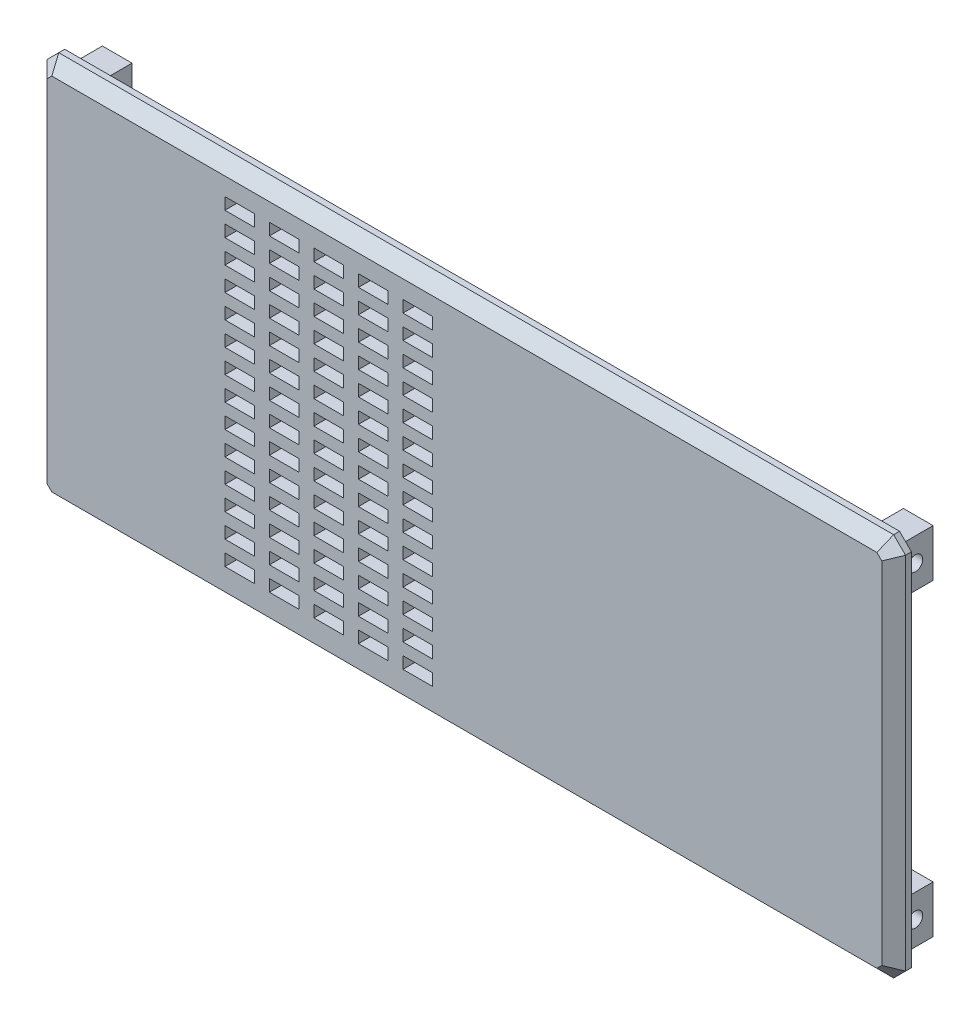
SolidWorks part; units mm, degrees
ref_plane "Спереди" through (0, 0, 0) normal (0, 0, 1) x (1, 0, 0)
ref_plane "Сверху" through (0, 0, 0) normal (0, 1, 0) x (1, 0, 0)
ref_plane "Справа" through (0, 0, 0) normal (1, 0, 0) x (0, 0, -1)
sketch "Эскиз1" plane through (0, 0, 0) normal (0, 0, 1) x (1, 0, 0)
  line L0 (-72.35, 30.35) -> (-70.35, 32.35)
  line L1 (70.35, -32.35) -> (-70.35, -32.35)
  line L2 (72.35, -30.35) -> (72.35, 30.35)
  line L3 (70.35, 32.35) -> (-70.35, 32.35)
  line L4 (-72.35, -30.35) -> (-72.35, 30.35)
  line L5 (-72.35, -30.35) -> (-70.35, -32.35)
  line L6 (70.35, -32.35) -> (72.35, -30.35)
  line L7 (70.35, 32.35) -> (72.35, 30.35)
extrude "Бобышка-Вытянуть1" add sketch "Эскиз1" along normal blind 3
sketch "Эскиз2" plane through (0, 0, 0) normal (0, 0, -1) x (-1, 0, 0)
  line L0 (-70, 30) -> (70, 30)
  line L1 (-70.35, 30.35) -> (70.35, 30.35) construction
  line L2 (-70.35, 30.35) -> (-70.35, -30.35) construction
  line L3 (-70.35, -30.35) -> (70.35, -30.35) construction
  line L4 (70.35, 30.35) -> (70.35, -30.35) construction
  line L5 (70, 30) -> (70, -30)
  line L6 (-70, -30) -> (70, -30)
  line L7 (-70, 30) -> (-70, -30)
  line L8 (-68, 28) -> (68, 28)
  line L9 (68, 28) -> (68, -28)
  line L10 (-68, -28) -> (68, -28)
  line L11 (-68, 28) -> (-68, -28)
  dimension "D1" = 0.35
  dimension "D2" = 2
extrude "Бобышка-Вытянуть2" add sketch "Эскиз2" along normal blind 2
sketch "Эскиз3" plane through (0, 0, 0) normal (0, 0, -1) x (-1, 0, 0)
  line L0 (-72.35, 0) -> (72.35, 0) construction
  line L1 (-72.35, -30.35) -> (-72.35, 30.35) construction
  line L2 (72.35, 30.35) -> (72.35, -30.35) construction
  line L3 (0, 32.35) -> (0, -32.35) construction
  line L4 (-70.35, 32.35) -> (70.35, 32.35) construction
  line L5 (70.35, -32.35) -> (-70.35, -32.35) construction
  line L6 (-70, 30) -> (-70, -30) construction
  line L7 (-70, 30) -> (-65, 30)
  line L8 (-70, 30) -> (-70, 22)
  line L9 (-70, 22) -> (-65, 22)
  line L10 (-65, 30) -> (-65, 22)
  line L11 (70, 30) -> (-70, 30) construction
  line L12 (-65, -30) -> (-65, -22)
  line L13 (-70, -22) -> (-65, -22)
  line L14 (-70, -30) -> (-70, -22)
  line L15 (-70, -30) -> (-65, -30)
  line L16 (70, -30) -> (65, -30)
  line L17 (70, -30) -> (70, -22)
  line L18 (70, -22) -> (65, -22)
  line L19 (65, -30) -> (65, -22)
  line L20 (65, 30) -> (65, 22)
  line L21 (70, 22) -> (65, 22)
  line L22 (70, 30) -> (70, 22)
  line L23 (70, 30) -> (65, 30)
  dimension "D1" = 5
  dimension "D2" = 8
extrude "Бобышка-Вытянуть3" add sketch "Эскиз3" along normal blind 6
sketch "Эскиз4" plane through (70, 0, 0) normal (1, 0, 0) x (0, 0, -1)
  line L0 (0, 30) -> (6, 22) construction
  line L1 (6, 30) -> (0, 22) construction
  line L2 (0, -30.35) -> (0, 30.35) construction
  line L3 (6, -22) -> (0, -30) construction
  line L4 (6, -30) -> (0, -22) construction
  line L5 (0, 30) -> (0, -30) construction
  line L6 (2, -22) -> (0, -22) construction
  line L7 (2, 22) -> (0, 22) construction
  circle A0 centre (3, 26) radius 1.25
  circle A1 centre (3, -26) radius 1.25
  dimension "D1" = 2.5
extrude "Вырез-Вытянуть1" cut sketch "Эскиз4" against normal up to surface (140 mm away)
sketch "Эскиз6" plane through (0, 0, 3) normal (0, 0, 1) x (1, 0, 0)
  line L0 (-5.35, -32.35) -> (-5.35, 32.35) construction
  line L1 (-70.35, -32.35) -> (70.35, -32.35) construction
  line L2 (70.35, 32.35) -> (-70.35, 32.35) construction
  line L3 (-40.35, -32.35) -> (-40.35, 32.35) construction
  line L4 (-72.35, 30.35) -> (-72.35, -30.35) construction
  line L5 (-40.35, 27.35) -> (-5.35, 27.35) construction
  line L6 (-27.85, 27.35) -> (-27.85, 25.35)
  line L7 (-40.35, 27.35) -> (-35.35, 27.35)
  line L8 (-40.35, 27.35) -> (-40.35, 25.35)
  line L9 (-40.35, 25.35) -> (-35.35, 25.35)
  line L10 (-35.35, 27.35) -> (-35.35, 25.35)
  line L11 (-32.85, 27.35) -> (-27.85, 27.35)
  line L12 (-32.85, 25.35) -> (-27.85, 25.35)
  line L13 (-32.85, 27.35) -> (-32.85, 25.35)
  line L14 (-20.35, 27.35) -> (-20.35, 25.35)
  line L15 (-25.35, 27.35) -> (-20.35, 27.35)
  line L16 (-25.35, 25.35) -> (-20.35, 25.35)
  line L17 (-25.35, 27.35) -> (-25.35, 25.35)
  line L18 (-12.85, 27.35) -> (-12.85, 25.35)
  line L19 (-17.85, 27.35) -> (-12.85, 27.35)
  line L20 (-17.85, 25.35) -> (-12.85, 25.35)
  line L21 (-17.85, 27.35) -> (-17.85, 25.35)
  line L22 (-5.35, 27.35) -> (-5.35, 25.35)
  line L23 (-10.35, 27.35) -> (-5.35, 27.35)
  line L24 (-10.35, 25.35) -> (-5.35, 25.35)
  line L25 (-10.35, 27.35) -> (-10.35, 25.35)
  line L26 (-27.85, 23.35) -> (-27.85, 21.35)
  line L27 (-32.85, 23.35) -> (-27.85, 23.35)
  line L28 (-32.85, 21.35) -> (-27.85, 21.35)
  line L29 (-32.85, 23.35) -> (-32.85, 21.35)
  line L30 (-20.35, 23.35) -> (-20.35, 21.35)
  line L31 (-25.35, 23.35) -> (-20.35, 23.35)
  line L32 (-25.35, 21.35) -> (-20.35, 21.35)
  line L33 (-25.35, 23.35) -> (-25.35, 21.35)
  line L34 (-12.85, 23.35) -> (-12.85, 21.35)
  line L35 (-17.85, 23.35) -> (-12.85, 23.35)
  line L36 (-17.85, 21.35) -> (-12.85, 21.35)
  line L37 (-17.85, 23.35) -> (-17.85, 21.35)
  line L38 (-5.35, 23.35) -> (-5.35, 21.35)
  line L39 (-10.35, 23.35) -> (-5.35, 23.35)
  line L40 (-10.35, 21.35) -> (-5.35, 21.35)
  line L41 (-10.35, 23.35) -> (-10.35, 21.35)
  line L42 (-27.85, 19.35) -> (-27.85, 17.35)
  line L43 (-32.85, 19.35) -> (-27.85, 19.35)
  line L44 (-32.85, 17.35) -> (-27.85, 17.35)
  line L45 (-32.85, 19.35) -> (-32.85, 17.35)
  line L46 (-20.35, 19.35) -> (-20.35, 17.35)
  line L47 (-25.35, 19.35) -> (-20.35, 19.35)
  line L48 (-25.35, 17.35) -> (-20.35, 17.35)
  line L49 (-25.35, 19.35) -> (-25.35, 17.35)
  line L50 (-12.85, 19.35) -> (-12.85, 17.35)
  line L51 (-17.85, 19.35) -> (-12.85, 19.35)
  line L52 (-17.85, 17.35) -> (-12.85, 17.35)
  line L53 (-17.85, 19.35) -> (-17.85, 17.35)
  line L54 (-5.35, 19.35) -> (-5.35, 17.35)
  line L55 (-10.35, 19.35) -> (-5.35, 19.35)
  line L56 (-10.35, 17.35) -> (-5.35, 17.35)
  line L57 (-10.35, 19.35) -> (-10.35, 17.35)
  line L58 (-27.85, 15.35) -> (-27.85, 13.35)
  line L59 (-32.85, 15.35) -> (-27.85, 15.35)
  line L60 (-32.85, 13.35) -> (-27.85, 13.35)
  line L61 (-32.85, 15.35) -> (-32.85, 13.35)
  line L62 (-20.35, 15.35) -> (-20.35, 13.35)
  line L63 (-25.35, 15.35) -> (-20.35, 15.35)
  line L64 (-25.35, 13.35) -> (-20.35, 13.35)
  line L65 (-25.35, 15.35) -> (-25.35, 13.35)
  line L66 (-12.85, 15.35) -> (-12.85, 13.35)
  line L67 (-17.85, 15.35) -> (-12.85, 15.35)
  line L68 (-17.85, 13.35) -> (-12.85, 13.35)
  line L69 (-17.85, 15.35) -> (-17.85, 13.35)
  line L70 (-5.35, 15.35) -> (-5.35, 13.35)
  line L71 (-10.35, 15.35) -> (-5.35, 15.35)
  line L72 (-10.35, 13.35) -> (-5.35, 13.35)
  line L73 (-10.35, 15.35) -> (-10.35, 13.35)
  line L74 (-27.85, 11.35) -> (-27.85, 9.35)
  line L75 (-32.85, 11.35) -> (-27.85, 11.35)
  line L76 (-32.85, 9.35) -> (-27.85, 9.35)
  line L77 (-32.85, 11.35) -> (-32.85, 9.35)
  line L78 (-20.35, 11.35) -> (-20.35, 9.35)
  line L79 (-25.35, 11.35) -> (-20.35, 11.35)
  line L80 (-25.35, 9.35) -> (-20.35, 9.35)
  line L81 (-25.35, 11.35) -> (-25.35, 9.35)
  line L82 (-12.85, 11.35) -> (-12.85, 9.35)
  line L83 (-17.85, 11.35) -> (-12.85, 11.35)
  line L84 (-17.85, 9.35) -> (-12.85, 9.35)
  line L85 (-17.85, 11.35) -> (-17.85, 9.35)
  line L86 (-5.35, 11.35) -> (-5.35, 9.35)
  line L87 (-10.35, 11.35) -> (-5.35, 11.35)
  line L88 (-10.35, 9.35) -> (-5.35, 9.35)
  line L89 (-10.35, 11.35) -> (-10.35, 9.35)
  line L90 (-27.85, 7.35) -> (-27.85, 5.35)
  line L91 (-32.85, 7.35) -> (-27.85, 7.35)
  line L92 (-32.85, 5.35) -> (-27.85, 5.35)
  line L93 (-32.85, 7.35) -> (-32.85, 5.35)
  line L94 (-20.35, 7.35) -> (-20.35, 5.35)
  line L95 (-25.35, 7.35) -> (-20.35, 7.35)
  line L96 (-25.35, 5.35) -> (-20.35, 5.35)
  line L97 (-25.35, 7.35) -> (-25.35, 5.35)
  line L98 (-12.85, 7.35) -> (-12.85, 5.35)
  line L99 (-17.85, 7.35) -> (-12.85, 7.35)
  line L100 (-17.85, 5.35) -> (-12.85, 5.35)
  line L101 (-17.85, 7.35) -> (-17.85, 5.35)
  line L102 (-5.35, 7.35) -> (-5.35, 5.35)
  line L103 (-10.35, 7.35) -> (-5.35, 7.35)
  line L104 (-10.35, 5.35) -> (-5.35, 5.35)
  line L105 (-10.35, 7.35) -> (-10.35, 5.35)
  line L106 (-27.85, 3.35) -> (-27.85, 1.35)
  line L107 (-32.85, 3.35) -> (-27.85, 3.35)
  line L108 (-32.85, 1.35) -> (-27.85, 1.35)
  line L109 (-32.85, 3.35) -> (-32.85, 1.35)
  line L110 (-20.35, 3.35) -> (-20.35, 1.35)
  line L111 (-25.35, 3.35) -> (-20.35, 3.35)
  line L112 (-25.35, 1.35) -> (-20.35, 1.35)
  line L113 (-25.35, 3.35) -> (-25.35, 1.35)
  line L114 (-12.85, 3.35) -> (-12.85, 1.35)
  line L115 (-17.85, 3.35) -> (-12.85, 3.35)
  line L116 (-17.85, 1.35) -> (-12.85, 1.35)
  line L117 (-17.85, 3.35) -> (-17.85, 1.35)
  line L118 (-5.35, 3.35) -> (-5.35, 1.35)
  line L119 (-10.35, 3.35) -> (-5.35, 3.35)
  line L120 (-10.35, 1.35) -> (-5.35, 1.35)
  line L121 (-10.35, 3.35) -> (-10.35, 1.35)
  line L122 (-27.85, -0.65) -> (-27.85, -2.65)
  line L123 (-32.85, -0.65) -> (-27.85, -0.65)
  line L124 (-32.85, -2.65) -> (-27.85, -2.65)
  line L125 (-32.85, -0.65) -> (-32.85, -2.65)
  line L126 (-20.35, -0.65) -> (-20.35, -2.65)
  line L127 (-25.35, -0.65) -> (-20.35, -0.65)
  line L128 (-25.35, -2.65) -> (-20.35, -2.65)
  line L129 (-25.35, -0.65) -> (-25.35, -2.65)
  line L130 (-12.85, -0.65) -> (-12.85, -2.65)
  line L131 (-17.85, -0.65) -> (-12.85, -0.65)
  line L132 (-17.85, -2.65) -> (-12.85, -2.65)
  line L133 (-17.85, -0.65) -> (-17.85, -2.65)
  line L134 (-5.35, -0.65) -> (-5.35, -2.65)
  line L135 (-10.35, -0.65) -> (-5.35, -0.65)
  line L136 (-10.35, -2.65) -> (-5.35, -2.65)
  line L137 (-10.35, -0.65) -> (-10.35, -2.65)
  line L138 (-27.85, -4.65) -> (-27.85, -6.65)
  line L139 (-32.85, -4.65) -> (-27.85, -4.65)
  line L140 (-32.85, -6.65) -> (-27.85, -6.65)
  line L141 (-32.85, -4.65) -> (-32.85, -6.65)
  line L142 (-20.35, -4.65) -> (-20.35, -6.65)
  line L143 (-25.35, -4.65) -> (-20.35, -4.65)
  line L144 (-25.35, -6.65) -> (-20.35, -6.65)
  line L145 (-25.35, -4.65) -> (-25.35, -6.65)
  line L146 (-12.85, -4.65) -> (-12.85, -6.65)
  line L147 (-17.85, -4.65) -> (-12.85, -4.65)
  line L148 (-17.85, -6.65) -> (-12.85, -6.65)
  line L149 (-17.85, -4.65) -> (-17.85, -6.65)
  line L150 (-5.35, -4.65) -> (-5.35, -6.65)
  line L151 (-10.35, -4.65) -> (-5.35, -4.65)
  line L152 (-10.35, -6.65) -> (-5.35, -6.65)
  line L153 (-10.35, -4.65) -> (-10.35, -6.65)
  line L154 (-27.85, -8.65) -> (-27.85, -10.65)
  line L155 (-32.85, -8.65) -> (-27.85, -8.65)
  line L156 (-32.85, -10.65) -> (-27.85, -10.65)
  line L157 (-32.85, -8.65) -> (-32.85, -10.65)
  line L158 (-20.35, -8.65) -> (-20.35, -10.65)
  line L159 (-25.35, -8.65) -> (-20.35, -8.65)
  line L160 (-25.35, -10.65) -> (-20.35, -10.65)
  line L161 (-25.35, -8.65) -> (-25.35, -10.65)
  line L162 (-12.85, -8.65) -> (-12.85, -10.65)
  line L163 (-17.85, -8.65) -> (-12.85, -8.65)
  line L164 (-17.85, -10.65) -> (-12.85, -10.65)
  line L165 (-17.85, -8.65) -> (-17.85, -10.65)
  line L166 (-5.35, -8.65) -> (-5.35, -10.65)
  line L167 (-10.35, -8.65) -> (-5.35, -8.65)
  line L168 (-10.35, -10.65) -> (-5.35, -10.65)
  line L169 (-10.35, -8.65) -> (-10.35, -10.65)
  line L170 (-27.85, -12.65) -> (-27.85, -14.65)
  line L171 (-32.85, -12.65) -> (-27.85, -12.65)
  line L172 (-32.85, -14.65) -> (-27.85, -14.65)
  line L173 (-32.85, -12.65) -> (-32.85, -14.65)
  line L174 (-20.35, -12.65) -> (-20.35, -14.65)
  line L175 (-25.35, -12.65) -> (-20.35, -12.65)
  line L176 (-25.35, -14.65) -> (-20.35, -14.65)
  line L177 (-25.35, -12.65) -> (-25.35, -14.65)
  line L178 (-12.85, -12.65) -> (-12.85, -14.65)
  line L179 (-17.85, -12.65) -> (-12.85, -12.65)
  line L180 (-17.85, -14.65) -> (-12.85, -14.65)
  line L181 (-17.85, -12.65) -> (-17.85, -14.65)
  line L182 (-5.35, -12.65) -> (-5.35, -14.65)
  line L183 (-10.35, -12.65) -> (-5.35, -12.65)
  line L184 (-10.35, -14.65) -> (-5.35, -14.65)
  line L185 (-10.35, -12.65) -> (-10.35, -14.65)
  line L186 (-27.85, -16.65) -> (-27.85, -18.65)
  line L187 (-32.85, -16.65) -> (-27.85, -16.65)
  line L188 (-32.85, -18.65) -> (-27.85, -18.65)
  line L189 (-32.85, -16.65) -> (-32.85, -18.65)
  line L190 (-20.35, -16.65) -> (-20.35, -18.65)
  line L191 (-25.35, -16.65) -> (-20.35, -16.65)
  line L192 (-25.35, -18.65) -> (-20.35, -18.65)
  line L193 (-25.35, -16.65) -> (-25.35, -18.65)
  line L194 (-12.85, -16.65) -> (-12.85, -18.65)
  line L195 (-17.85, -16.65) -> (-12.85, -16.65)
  line L196 (-17.85, -18.65) -> (-12.85, -18.65)
  line L197 (-17.85, -16.65) -> (-17.85, -18.65)
  line L198 (-5.35, -16.65) -> (-5.35, -18.65)
  line L199 (-10.35, -16.65) -> (-5.35, -16.65)
  line L200 (-10.35, -18.65) -> (-5.35, -18.65)
  line L201 (-10.35, -16.65) -> (-10.35, -18.65)
  line L202 (-27.85, -20.65) -> (-27.85, -22.65)
  line L203 (-32.85, -20.65) -> (-27.85, -20.65)
  line L204 (-32.85, -22.65) -> (-27.85, -22.65)
  line L205 (-32.85, -20.65) -> (-32.85, -22.65)
  line L206 (-20.35, -20.65) -> (-20.35, -22.65)
  line L207 (-25.35, -20.65) -> (-20.35, -20.65)
  line L208 (-25.35, -22.65) -> (-20.35, -22.65)
  line L209 (-25.35, -20.65) -> (-25.35, -22.65)
  line L210 (-12.85, -20.65) -> (-12.85, -22.65)
  line L211 (-17.85, -20.65) -> (-12.85, -20.65)
  line L212 (-17.85, -22.65) -> (-12.85, -22.65)
  line L213 (-17.85, -20.65) -> (-17.85, -22.65)
  line L214 (-5.35, -20.65) -> (-5.35, -22.65)
  line L215 (-10.35, -20.65) -> (-5.35, -20.65)
  line L216 (-10.35, -22.65) -> (-5.35, -22.65)
  line L217 (-10.35, -20.65) -> (-10.35, -22.65)
  line L218 (-27.85, -24.65) -> (-27.85, -26.65)
  line L219 (-32.85, -24.65) -> (-27.85, -24.65)
  line L220 (-32.85, -26.65) -> (-27.85, -26.65)
  line L221 (-32.85, -24.65) -> (-32.85, -26.65)
  line L222 (-20.35, -24.65) -> (-20.35, -26.65)
  line L223 (-25.35, -24.65) -> (-20.35, -24.65)
  line L224 (-25.35, -26.65) -> (-20.35, -26.65)
  line L225 (-25.35, -24.65) -> (-25.35, -26.65)
  line L226 (-12.85, -24.65) -> (-12.85, -26.65)
  line L227 (-17.85, -24.65) -> (-12.85, -24.65)
  line L228 (-17.85, -26.65) -> (-12.85, -26.65)
  line L229 (-17.85, -24.65) -> (-17.85, -26.65)
  line L230 (-5.35, -24.65) -> (-5.35, -26.65)
  line L231 (-10.35, -24.65) -> (-5.35, -24.65)
  line L232 (-10.35, -26.65) -> (-5.35, -26.65)
  line L233 (-10.35, -24.65) -> (-10.35, -26.65)
  line L234 (-35.35, 23.35) -> (-35.35, 21.35)
  line L235 (-40.35, 23.35) -> (-35.35, 23.35)
  line L236 (-40.35, 21.35) -> (-35.35, 21.35)
  line L237 (-40.35, 23.35) -> (-40.35, 21.35)
  line L238 (-35.35, 19.35) -> (-35.35, 17.35)
  line L239 (-40.35, 19.35) -> (-35.35, 19.35)
  line L240 (-40.35, 17.35) -> (-35.35, 17.35)
  line L241 (-40.35, 19.35) -> (-40.35, 17.35)
  line L242 (-35.35, 15.35) -> (-35.35, 13.35)
  line L243 (-40.35, 15.35) -> (-35.35, 15.35)
  line L244 (-40.35, 13.35) -> (-35.35, 13.35)
  line L245 (-40.35, 15.35) -> (-40.35, 13.35)
  line L246 (-35.35, 11.35) -> (-35.35, 9.35)
  line L247 (-40.35, 11.35) -> (-35.35, 11.35)
  line L248 (-40.35, 9.35) -> (-35.35, 9.35)
  line L249 (-40.35, 11.35) -> (-40.35, 9.35)
  line L250 (-35.35, 7.35) -> (-35.35, 5.35)
  line L251 (-40.35, 7.35) -> (-35.35, 7.35)
  line L252 (-40.35, 5.35) -> (-35.35, 5.35)
  line L253 (-40.35, 7.35) -> (-40.35, 5.35)
  line L254 (-35.35, 3.35) -> (-35.35, 1.35)
  line L255 (-40.35, 3.35) -> (-35.35, 3.35)
  line L256 (-40.35, 1.35) -> (-35.35, 1.35)
  line L257 (-40.35, 3.35) -> (-40.35, 1.35)
  line L258 (-35.35, -0.65) -> (-35.35, -2.65)
  line L259 (-40.35, -0.65) -> (-35.35, -0.65)
  line L260 (-40.35, -2.65) -> (-35.35, -2.65)
  line L261 (-40.35, -0.65) -> (-40.35, -2.65)
  line L262 (-35.35, -4.65) -> (-35.35, -6.65)
  line L263 (-40.35, -4.65) -> (-35.35, -4.65)
  line L264 (-40.35, -6.65) -> (-35.35, -6.65)
  line L265 (-40.35, -4.65) -> (-40.35, -6.65)
  line L266 (-35.35, -8.65) -> (-35.35, -10.65)
  line L267 (-40.35, -8.65) -> (-35.35, -8.65)
  line L268 (-40.35, -10.65) -> (-35.35, -10.65)
  line L269 (-40.35, -8.65) -> (-40.35, -10.65)
  line L270 (-35.35, -12.65) -> (-35.35, -14.65)
  line L271 (-40.35, -12.65) -> (-35.35, -12.65)
  line L272 (-40.35, -14.65) -> (-35.35, -14.65)
  line L273 (-40.35, -12.65) -> (-40.35, -14.65)
  line L274 (-35.35, -16.65) -> (-35.35, -18.65)
  line L275 (-40.35, -16.65) -> (-35.35, -16.65)
  line L276 (-40.35, -18.65) -> (-35.35, -18.65)
  line L277 (-40.35, -16.65) -> (-40.35, -18.65)
  line L278 (-35.35, -20.65) -> (-35.35, -22.65)
  line L279 (-40.35, -20.65) -> (-35.35, -20.65)
  line L280 (-40.35, -22.65) -> (-35.35, -22.65)
  line L281 (-40.35, -20.65) -> (-40.35, -22.65)
  line L282 (-35.35, -24.65) -> (-35.35, -26.65)
  line L283 (-40.35, -24.65) -> (-35.35, -24.65)
  line L284 (-40.35, -26.65) -> (-35.35, -26.65)
  line L285 (-40.35, -24.65) -> (-40.35, -26.65)
  dimension "D1" = 32
  dimension "D2" = 35
  dimension "D3" = 5
  dimension "D4" = 5
  dimension "D5" = 2
  dimension "D6" = 5
  dimension "D7" = 14
extrude "Вырез-Вытянуть2" cut sketch "Эскиз6" against normal up to surface (3 mm away) up to face at (0, 0, 0)
chamfer "Фаска1" distance 2 angle 45 8 edges at (71.35, 31.35, 3) (72.35, 0, 3) (71.35, -31.35, 3) (0, -32.35, 3) (-71.35, -31.35, 3) (-72.35, 0, 3) (-71.35, 31.35, 3) (0, 32.35, 3)
